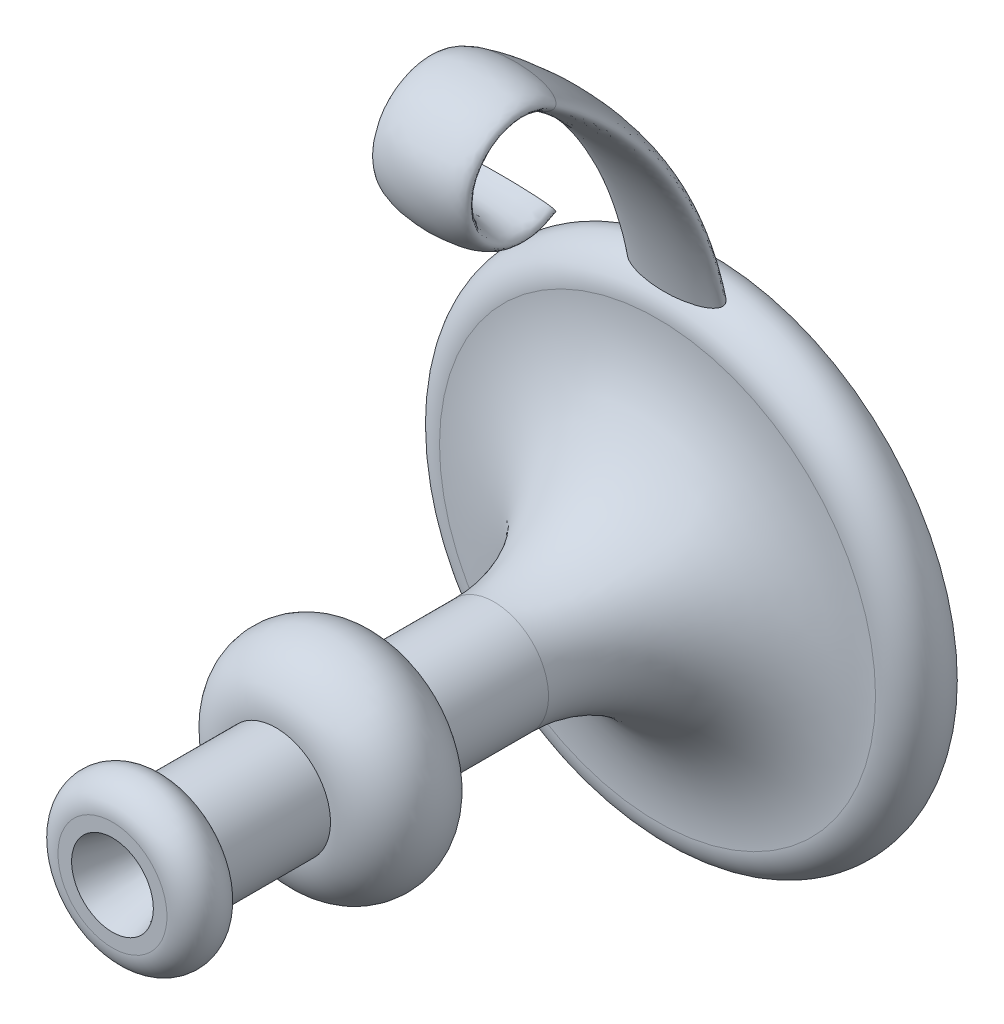
SolidWorks part; units mm, degrees
ref_plane "Front Plane" through (0, 0, 0) normal (1, 0, 0) x (0, 1, 0)
ref_plane "Top Plane" through (0, 0, 0) normal (0, 0, 1) x (0, 1, 0)
ref_plane "Right Plane" through (0, 0, 0) normal (0, 1, 0) x (-1, 0, 0)
sketch "Sketch1" plane through (0, 0, 0) normal (1, 0, 0) x (0, 1, 0)
  line L0 (0, 0) -> (0, 220)
  line L1 (0, 220) -> (20, 220)
  line L2 (0, 0) -> (90, 0)
  line L3 (20, 200) -> (20, 160)
  line L4 (20, 120) -> (20, 80)
  arc A0 (20, 220) -> (20, 200) centre (20, 210) cw
  arc A1 (20, 160) -> (20, 120) centre (20, 140) cw
  arc A7 (20, 80) -> (80, 20) centre (80, 80) ccw
  arc A8 (80, 20) -> (90, 0) centre (80, 7.5) cw
  dimension "D4" = 10
  dimension "D5" = 20
  dimension "D7" = 60
  dimension "D8" = 12.5
  dimension "D1" = 220
  dimension "D2" = 20
  dimension "D3" = 90
  dimension "D6" = 40
  dimension "D9" = 80
revolve "Revolve1" add sketch "Sketch1" angle 360 about L0
sketch "Sketch5" plane through (0, 0, 0) normal (1, 0, 0) x (0, 1, 0)
  line L0 (0, 10) -> (60, 10)
  line L1 (0, 227.4356) -> (0, 175.1288) construction
  arc A0 (60, 10) -> (183.5921, 75) centre (60, 160) ccw
  arc A1 (183.5921, 75) -> (150.6342, 75) centre (167.1131, 86.3333) ccw
  point P8 (0, 0)
  point P9 (0, 0)
  point P10 (0, 0)
  dimension "D2" = 150
  dimension "D4" = 20
  dimension "D1" = 60
  dimension "D3" = 65
  dimension "D5" = 10
sketch "Sketch6" plane through (0, 0, 0) normal (0, 1, 0) x (-1, 0, 0)
  ellipse E0 centre (0, 10) end of major axis (-17.5, 10) minor radius 5
  dimension "D1" = 35
  dimension "D2" = 10
sweep "Sweep1" add profiles "Sketch6" path "Sketch5"
sketch "Sketch7" plane through (0, 0, 220) normal (0, 0, 1) x (1, 0, 0)
  circle A0 centre (0, 0) radius 15
  dimension "D1" = 30
extrude "Cut-Extrude1" cut sketch "Sketch7" against normal blind 25 draft 15
